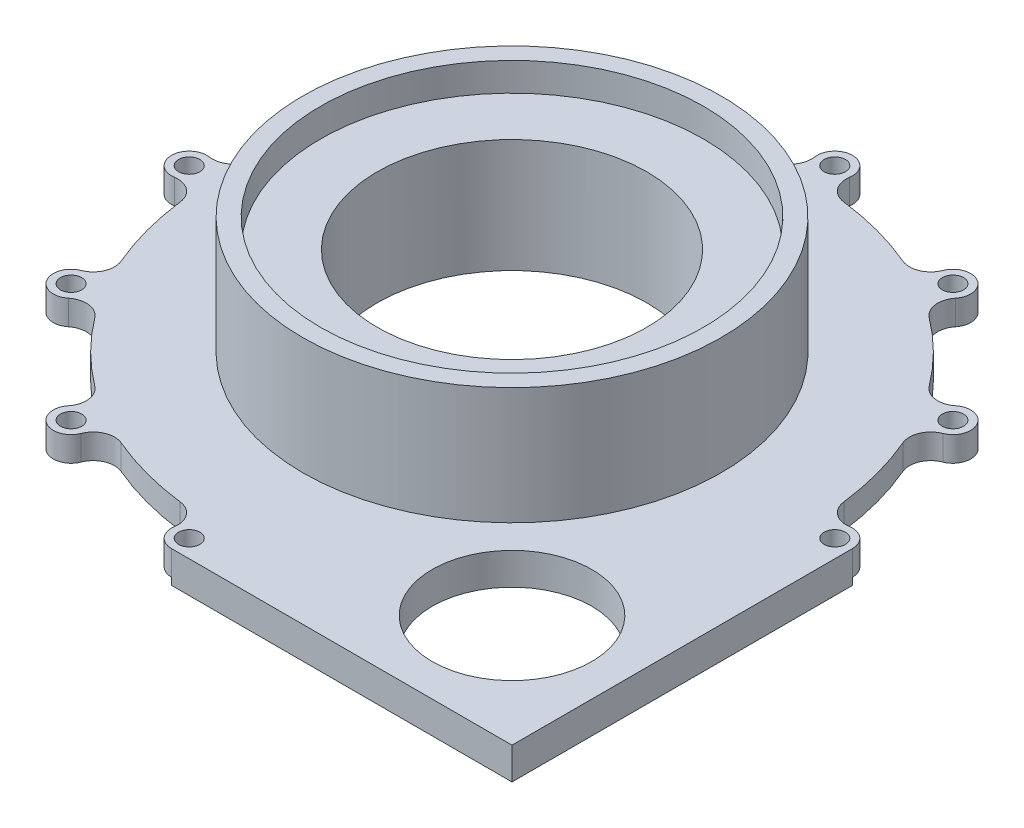
SolidWorks part; units mm, degrees
ref_plane "Front Plane" through (0, 0, 0) normal (0, 0, 1) x (1, 0, 0)
ref_plane "Top Plane" through (0, 0, 0) normal (0, 1, 0) x (1, 0, 0)
ref_plane "Right Plane" through (0, 0, 0) normal (1, 0, 0) x (0, 0, -1)
sketch "Sketch1" plane through (0, 0, 0) normal (0, 0, 1) x (1, 0, 0)
  line L0 (0, 0) -> (-80, 0)
  line L1 (-80, 0) -> (-80, 2)
  line L2 (-80, 2) -> (-84, 2)
  line L3 (-84, 2) -> (-84, 9)
  line L4 (-84, 9) -> (-59, 9)
  line L5 (-59, 9) -> (-59, 42)
  line L6 (-59, 42) -> (0, 42)
  line L7 (0, 42) -> (0, 0)
  dimension "D1" = 42
  dimension "D2" = 59
  dimension "D3" = 7
  dimension "D4" = 2
  dimension "D5" = 80
  dimension "D6" = 84
revolve "Revolve1" add sketch "Sketch1" angle 360 about L7
hole_wizard "Hole1" positions "Sketch2" profile "Sketch3" legacy end condition up to next
sketch "Sketch2" plane through (0, 0, 0) normal (0, -1, 0) x (-1, 0, 0)
  point P0 (0, 0)
sketch "Sketch3" plane through (0, 0, 0) normal (1, 0, 0) x (0, 0, -1)
  line L0 (0, 0) -> (0, 42)
  line L1 (0, 42) -> (38, 42)
  line L2 (38, 42) -> (38, 2)
  line L3 (38, 2) -> (47, 2)
  line L4 (47, 2) -> (47, 0)
  line L5 (47, 0) -> (0, 0)
  line L6 (0, 110) -> (0, -10) construction
  dimension "Diameter" = 76
  dimension "Depth" = 42
  dimension "C-Bore Diameter" = 94
  dimension "C-Bore Depth" = 2
hole_wizard "Hole2" positions "Sketch4" profile "Sketch5" legacy
sketch "Sketch4" plane through (0, 42, 0) normal (0, 1, 0) x (1, 0, 0)
  point P0 (0, 0)
sketch "Sketch5" plane through (0, 42, 0) normal (1, 0, 0) x (0, 0, 1)
  line L0 (0, 0) -> (0, 42)
  line L1 (0, 42) -> (33, 42)
  line L2 (33, 42) -> (33, 8)
  line L3 (33, 8) -> (54, 8)
  line L4 (54, 8) -> (54, 0)
  line L5 (54, 0) -> (0, 0)
  line L6 (0, 110) -> (0, -10) construction
  dimension "Diameter" = 66
  dimension "Depth" = 42
  dimension "C-Bore Diameter" = 108
  dimension "C-Bore Depth" = 8
sketch "Sketch6" plane through (0, 0, 0) normal (0, -1, 0) x (1, 0, 0)
  line L0 (50, 0) -> (77, 0) construction
  line L1 (49.96, 2) -> (76.974, 2)
  line L2 (49.96, -2) -> (76.974, -2)
  line L3 (42.2666, -26.712) -> (65.6615, -40.2191)
  line L4 (44.2666, -23.2479) -> (67.6615, -36.755)
  line L5 (23.2479, -44.2666) -> (36.755, -67.6615)
  line L6 (26.712, -42.2666) -> (40.2191, -65.6615)
  line L7 (-2, -49.96) -> (-2, -76.974)
  line L8 (2, -49.96) -> (2, -76.974)
  line L9 (-26.712, -42.2666) -> (-40.2191, -65.6615)
  line L10 (-23.2479, -44.2666) -> (-36.755, -67.6615)
  line L11 (-44.2666, -23.2479) -> (-67.6615, -36.755)
  line L12 (-42.2666, -26.712) -> (-65.6615, -40.2191)
  line L13 (-49.96, 2) -> (-76.974, 2)
  line L14 (-49.96, -2) -> (-76.974, -2)
  line L15 (-42.2666, 26.712) -> (-65.6615, 40.2191)
  line L16 (-44.2666, 23.2479) -> (-67.6615, 36.755)
  line L17 (-23.2479, 44.2666) -> (-36.755, 67.6615)
  line L18 (-26.712, 42.2666) -> (-40.2191, 65.6615)
  line L19 (2, 49.96) -> (2, 76.974)
  line L20 (-2, 49.96) -> (-2, 76.974)
  line L21 (26.712, 42.2666) -> (40.2191, 65.6615)
  line L22 (23.2479, 44.2666) -> (36.755, 67.6615)
  line L23 (44.2666, 23.2479) -> (67.6615, 36.755)
  line L24 (42.2666, 26.712) -> (65.6615, 40.2191)
  arc A0 (76.974, 2) -> (67.6615, 36.755) centre (0, 0) ccw
  arc A1 (49.96, 2) -> (44.2666, 23.2479) centre (0, 0) ccw
  arc A2 (42.2666, 26.712) -> (26.712, 42.2666) centre (0, 0) ccw
  arc A3 (65.6615, 40.2191) -> (40.2191, 65.6615) centre (0, 0) ccw
  arc A4 (23.2479, 44.2666) -> (2, 49.96) centre (0, 0) ccw
  arc A5 (36.755, 67.6615) -> (2, 76.974) centre (0, 0) ccw
  arc A6 (-2, 76.974) -> (-36.755, 67.6615) centre (0, 0) ccw
  arc A7 (-2, 49.96) -> (-23.2479, 44.2666) centre (0, 0) ccw
  arc A8 (-40.2191, 65.6615) -> (-65.6615, 40.2191) centre (0, 0) ccw
  arc A9 (-26.712, 42.2666) -> (-42.2666, 26.712) centre (0, 0) ccw
  arc A10 (-44.2666, 23.2479) -> (-49.96, 2) centre (0, 0) ccw
  arc A11 (-67.6615, 36.755) -> (-76.974, 2) centre (0, 0) ccw
  arc A12 (-49.96, -2) -> (-44.2666, -23.2479) centre (0, 0) ccw
  arc A13 (-76.974, -2) -> (-67.6615, -36.755) centre (0, 0) ccw
  arc A14 (-42.2666, -26.712) -> (-26.712, -42.2666) centre (0, 0) ccw
  arc A15 (-65.6615, -40.2191) -> (-40.2191, -65.6615) centre (0, 0) ccw
  arc A16 (-23.2479, -44.2666) -> (-2, -49.96) centre (0, 0) ccw
  arc A17 (-36.755, -67.6615) -> (-2, -76.974) centre (0, 0) ccw
  arc A18 (2, -49.96) -> (23.2479, -44.2666) centre (0, 0) ccw
  arc A19 (2, -76.974) -> (36.755, -67.6615) centre (0, 0) ccw
  arc A20 (40.2191, -65.6615) -> (65.6615, -40.2191) centre (0, 0) ccw
  arc A21 (26.712, -42.2666) -> (42.2666, -26.712) centre (0, 0) ccw
  arc A22 (67.6615, -36.755) -> (76.974, -2) centre (0, 0) ccw
  arc A23 (44.2666, -23.2479) -> (49.96, -2) centre (0, 0) ccw
  point P11 (0, 0)
  point P56 (0, 0)
  dimension "D1" = 100
  dimension "D2" = 154
  dimension "D3" = 4
  dimension "D4" = 12
extrude "Cut-Extrude1" cut sketch "Sketch6" against normal blind 2
fillet "Fillet1" radius 5 48 edges at (-67.6615, 1, -36.755) (-23.2479, 1, 44.2666) (-42.2666, 1, -26.712) (-23.2479, 1, -44.2666) (26.712, 1, -42.2666) (49.96, 1, -2) (44.2666, 1, 23.2479) (67.6615, 1, 36.755) (76.974, 1, -2) (23.2479, 1, 44.2666) (-76.974, 1, 2) (36.755, 1, -67.6615) (-2, 1, -76.974) (-40.2191, 1, -65.6615) (65.6615, 1, -40.2191) (42.2666, 1, -26.712) (23.2479, 1, -44.2666) (2, 1, -49.96) (44.2666, 1, -23.2479) (49.96, 1, 2) (42.2666, 1, 26.712) (40.2191, 1, 65.6615) (26.712, 1, 42.2666) (2, 1, 49.96) (-40.2191, 1, 65.6615) (-49.96, 1, -2) (-42.2666, 1, 26.712) (-49.96, 1, 2) (-2, 1, -49.96) (-26.712, 1, -42.2666) (-44.2666, 1, -23.2479) (-2, 1, 49.96) (-26.712, 1, 42.2666) (-44.2666, 1, 23.2479) (-67.6615, 1, 36.755) (-76.974, 1, -2) (-65.6615, 1, -40.2191) (-36.755, 1, -67.6615) (2, 1, -76.974) (40.2191, 1, -65.6615) (67.6615, 1, -36.755) (76.974, 1, 2) (65.6615, 1, 40.2191) (-65.6615, 1, 40.2191) (-36.755, 1, 67.6615) (-2, 1, 76.974) (36.755, 1, 67.6615) (2, 1, 76.974)
sketch "Sketch7" plane through (0, 9, 0) normal (0, 1, 0) x (1, 0, 0)
  line L0 (0, 0) -> (118.0114, 0) construction
  arc A0 (89.4219, -16.8736) -> (89.4219, 16.8736) centre (0, 0) ccw construction
  arc A1 (90.2458, -4.9428) -> (90.2458, 4.9428) centre (91, 0) ccw
  arc A2 (83.3846, 10.1492) -> (90.2458, 4.9428) centre (89.3407, 10.8741) ccw
  circle A3 centre (0, 0) radius 84 construction
  arc A4 (83.3846, -10.1492) -> (90.2458, -4.9428) centre (89.3407, -10.8741) cw
  arc A5 (83.3846, -10.1492) -> (83.3846, 10.1492) centre (0, 0) ccw
  circle A6 centre (91, 0) radius 3
  dimension "D1" = 182
  dimension "D2" = 10
  dimension "D3" = 12
  dimension "D4" = 6
extrude "Boss-Extrude1" add sketch "Sketch7" against normal up to surface (7 mm away) up to face at (0, 2, 80)
pattern_circular "CirPattern1" count 12 over 360 about axis through (0, 0, 0) along (0, 1, 0) of "Boss-Extrude1"
sketch "Sketch9" plane through (0, 9, 0) normal (0, 1, 0) x (1, 0, 0)
  line L0 (96, 0) -> (96, -96)
  line L1 (96, -96) -> (0, -96)
  line L2 (96, 0) -> (94, 0)
  line L3 (0, -96) -> (0, -94)
  line L4 (88, 0) -> (38, 0)
  line L5 (0, -88) -> (0, -38)
  arc A0 (90.2458, -4.9428) -> (90.2458, 4.9428) centre (91, 0) ccw construction
  arc A1 (-4.9428, -90.2458) -> (4.9428, -90.2458) centre (0, -91) ccw construction
  arc A2 (38, 0) -> (0, -38) centre (0, 0) cw
  circle A3 centre (0, 0) radius 38 construction
  circle A4 centre (91, 0) radius 3 construction
  circle A5 centre (0, -91) radius 3 construction
  arc A6 (88, 0) -> (94, 0) centre (91, 0) ccw
  arc A7 (0, -94) -> (0, -88) centre (0, -91) ccw
extrude "Boss-Extrude2" add sketch "Sketch9" against normal up to surface (9 mm away) up to face at (-60.1418, 0, 16.115)
hole_wizard "Hole3" positions "Sketch10" profile "Sketch11" legacy end condition up to next
sketch "Sketch10" plane through (0, 9, 0) normal (0, 1, 0) x (1, 0, 0)
  line L0 (0, 0) -> (64.3467, -64.3467) construction
  line L2 (0, 0) -> (0, -109.6493) construction
  circle A0 centre (0, 0) radius 91 construction
  point P0 (64.3467, -64.3467)
  point P18 (0, 0)
  dimension "D1" = 182
  dimension "D2" = 45
sketch "Sketch11" plane through (64.3467, 9, 64.3467) normal (1, 0, 0) x (0, 0, 1)
  line L0 (0, 0) -> (0, 9)
  line L1 (0, 9) -> (22.5, 9)
  line L2 (22.5, 9) -> (22.5, 0)
  line L3 (22.5, 0) -> (0, 0)
  line L4 (0, 110) -> (0, -10) construction
  dimension "Diameter" = 45
  dimension "Depth" = 9
